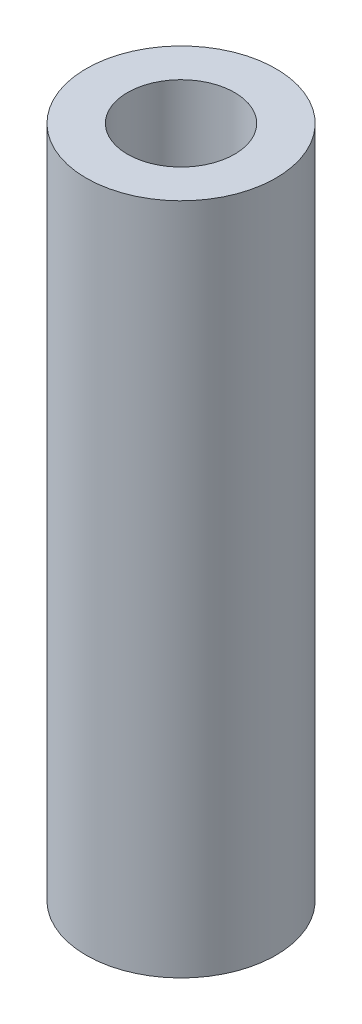
SolidWorks part; units mm, degrees
material "EPDM"
ref_plane "Płaszczyzna przednia" through (0, 0, 0) normal (0, 0, 1) x (1, 0, 0)
ref_plane "Płaszczyzna górna" through (0, 0, 0) normal (0, 1, 0) x (1, 0, 0)
ref_plane "Płaszczyzna prawa" through (0, 0, 0) normal (1, 0, 0) x (0, 0, -1)
sketch "Szkic1" plane through (0, 0, 0) normal (0, 0, 1) x (1, 0, 0)
  line L0 (0, 344.7443) -> (0, -336.9732) construction
  line L1 (35, 220) -> (62, 220)
  line L2 (35, 220) -> (35, -220)
  line L3 (35, -220) -> (62, -220)
  line L4 (62, 220) -> (62, -220)
  point P4 (35, 0)
  dimension "D1" = 62
  dimension "D2" = 35
  dimension "D3" = 440
revolve "Obrót1" add sketch "Szkic1" angle 360 about L0
